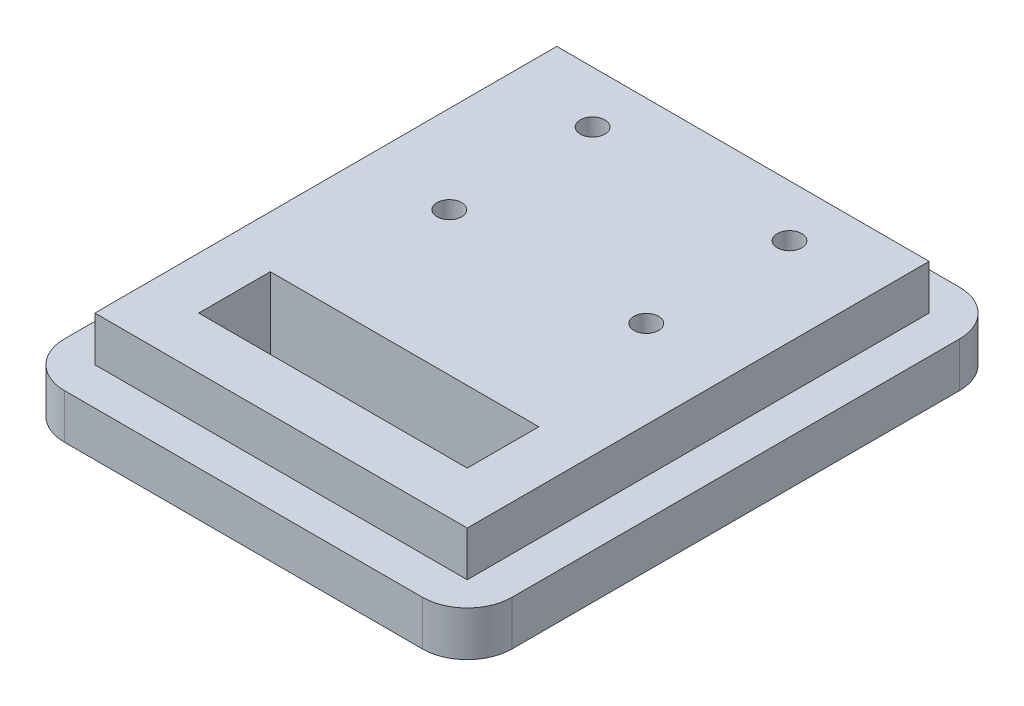
SolidWorks part; units mm, degrees
ref_plane "Front Plane" through (0, 0, 0) normal (0, 0, 1) x (1, 0, 0)
ref_plane "Top Plane" through (0, 0, 0) normal (0, 1, 0) x (1, 0, 0)
ref_plane "Right Plane" through (0, 0, 0) normal (1, 0, 0) x (0, 0, -1)
sketch "Sketch1" plane through (0, 0, 0) normal (0, 1, 0) x (1, 0, 0)
  line L1 (-15.875, -19.05) -> (15.875, -19.05)
  line L2 (-15.875, -19.05) -> (-15.875, 19.05)
  line L3 (-15.875, 19.05) -> (15.875, 19.05)
  line L4 (15.875, -19.05) -> (15.875, 19.05)
  line L5 (-15.875, -19.05) -> (15.875, 19.05) construction
  line L6 (-15.875, 19.05) -> (15.875, -19.05) construction
  point P0 (0, 0)
  dimension "D1" = 38.1
  dimension "D2" = 31.75
extrude "Boss-Extrude1" add sketch "Sketch1" along normal blind 6.35
sketch "Sketch2" plane through (0, 6.35, 0) normal (0, 1, 0) x (1, 0, 0)
  line L0 (6.985, 2.54) -> (0, 2.54) construction
  line L3 (0, 0) -> (0, 50000) construction
  line L4 (15.875, 19.05) -> (-15.875, 19.05) construction
  line L5 (-6.985, 2.54) -> (-6.985, 50002.54) construction
  line L6 (6.985, 7.62) -> (6.985, 50007.62) construction
  line L7 (-6.985, 12.7) -> (6.985, 12.7) construction
  circle A0 centre (-6.985, 2.54) radius 0.875
  circle A1 centre (6.985, 2.54) radius 0.875
  circle A2 centre (-6.985, 12.7) radius 0.875
  circle A3 centre (6.985, 12.7) radius 0.875
  point P21 (0, 12.7)
  dimension "D3" = 1.75
  dimension "D1" = 13.97
  dimension "D2" = 6.35
  dimension "D4" = 16.51
extrude "Cut-Extrude1" cut sketch "Sketch2" against normal through all
sketch "Sketch3" plane through (0, 6.35, 0) normal (0, 1, 0) x (1, 0, 0)
  line L0 (0, 0) -> (0, 50000) construction
  line L2 (-9.525, -12.7) -> (9.525, -12.7)
  line L3 (-9.525, -12.7) -> (-9.525, -7.62)
  line L4 (-9.525, -7.62) -> (9.525, -7.62)
  line L5 (9.525, -12.7) -> (9.525, -7.62)
  line L6 (-9.525, -12.7) -> (9.525, -7.62) construction
  line L7 (-9.525, -7.62) -> (9.525, -12.7) construction
  circle A0 centre (-6.985, 2.54) radius 0.875 construction
  point P3 (0, -10.16)
  dimension "D1" = 5.08
  dimension "D2" = 19.05
  dimension "D3" = 12.7
extrude "Cut-Extrude2" cut sketch "Sketch3" against normal through all
sketch "Sketch4" plane through (0, 6.35, 0) normal (0, 1, 0) x (1, 0, 0)
  line L0 (15.875, -19.05) -> (15.875, 19.05) construction
  line L1 (-13.208, -16.383) -> (13.208, -16.383)
  line L2 (-13.208, -16.383) -> (-13.208, 16.383)
  line L3 (-13.208, 16.383) -> (13.208, 16.383)
  line L4 (13.208, -16.383) -> (13.208, 16.383)
  line L5 (-13.208, -16.383) -> (13.208, 16.383) construction
  line L6 (-13.208, 16.383) -> (13.208, -16.383) construction
  line L7 (15.875, 19.05) -> (-15.875, 19.05) construction
  line L12 (15.875, -19.05) -> (15.875, 19.05)
  line L13 (15.875, 19.05) -> (-15.875, 19.05)
  line L14 (-15.875, 19.05) -> (-15.875, -19.05)
  line L15 (-15.875, -19.05) -> (15.875, -19.05)
  line L16 (15.875, -19.05) -> (15.875, 19.05)
  line L17 (15.875, 19.05) -> (-15.875, 19.05)
  line L18 (-15.875, 19.05) -> (-15.875, -19.05)
  line L19 (-15.875, -19.05) -> (15.875, -19.05)
  point P0 (0, 0)
  dimension "D1" = 2.667
  dimension "D2" = 2.667
  dimension "D3" = 0
extrude "Cut-Extrude3" cut sketch "Sketch4" against normal blind 3.175
fillet "Fillet1" radius 3.175 4 edges at (15.875, 1.5875, 19.05) (-15.875, 1.5875, 19.05) (15.875, 1.5875, -19.05) (-15.875, 1.5875, -19.05)
